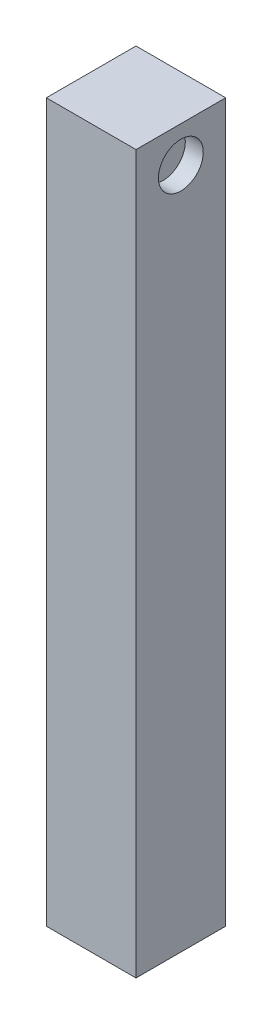
SolidWorks part; units mm, degrees
ref_plane "Front Plane" through (0, 0, 0) normal (0, 0, 1) x (1, 0, 0)
ref_plane "Top Plane" through (0, 0, 0) normal (0, 1, 0) x (1, 0, 0)
ref_plane "Right Plane" through (0, 0, 0) normal (1, 0, 0) x (0, 0, -1)
sketch "Sketch1" plane through (0, 0, 0) normal (1, 0, 0) x (0, 0, -1)
  line L1 (-50, -400) -> (50, -400)
  line L2 (-50, -400) -> (-50, 400)
  line L3 (-50, 400) -> (50, 400)
  line L4 (50, -400) -> (50, 400)
  line L5 (-50, -400) -> (50, 400) construction
  line L6 (-50, 400) -> (50, -400) construction
  point P0 (0, 0)
  dimension "D1" = 100
  dimension "D2" = 800
extrude "Boss-Extrude1" add sketch "Sketch1" along normal mid plane 100
sketch "Sketch2" plane through (50, 0, 0) normal (1, 0, 0) x (0, 0, -1)
  line L0 (0, 400) -> (0, 0) construction
  line L1 (50, 400) -> (-50, 400) construction
  circle A0 centre (0, 360) radius 25
  dimension "D1" = 50
  dimension "D2" = 40
extrude "Cut-Extrude1" cut sketch "Sketch2" against normal blind 20
